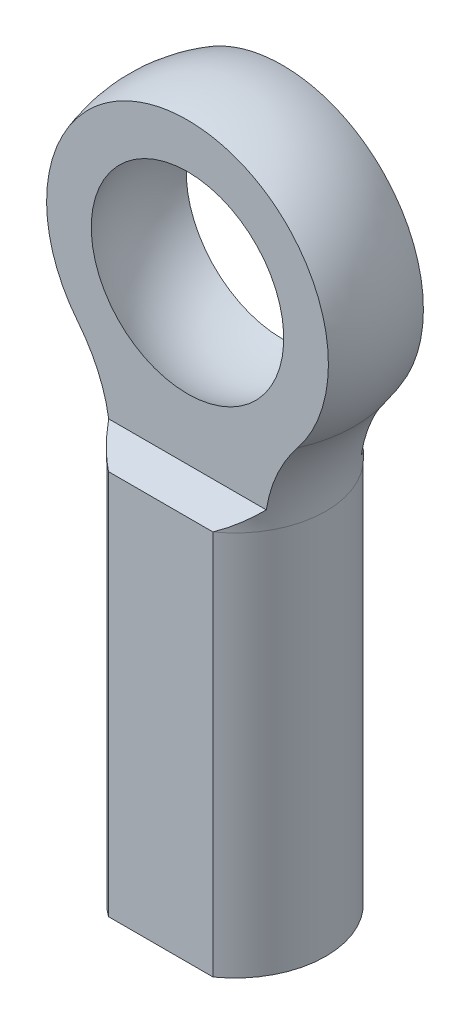
SolidWorks part; units mm, degrees
ref_plane "Front" through (0, 0, 0) normal (0, 0, 1) x (1, 0, 0)
ref_plane "Top" through (0, 0, 0) normal (0, 1, 0) x (1, 0, 0)
ref_plane "Right" through (0, 0, 0) normal (1, 0, 0) x (0, 0, -1)
sketch "Sketch1" plane through (0, 0, 0) normal (0, 0, 1) x (1, 0, 0)
  line L0 (0, 0) -> (0, -26.9875) construction
  line L1 (0, -26.9875) -> (4.7625, -26.9875) construction
  line L2 (4.7625, -26.9875) -> (4.7625, 0) construction
  line L3 (4.7625, 0) -> (0, 0) construction
  line L5 (0, 41.275) -> (0, 0) construction
  line L6 (0, 41.275) -> (14.2875, 41.275) construction
  line L7 (14.2875, 41.275) -> (14.2875, 26.9875) construction
  line L8 (-4.7625, -26.9875) -> (-4.7625, 0) construction
  line L9 (-8.7249, -26.9875) -> (8.7249, -26.9875) construction
  line L10 (8.7249, -26.9875) -> (8.7249, 10.0476) construction
  line L11 (-8.7249, -26.9875) -> (-8.7249, 10.0476) construction
  line L16 (4.8771, -27.4505) -> (4.7625, -27.4505) construction
  line L18 (4.7625, -27.9135) -> (4.7625, -26.9875) construction
  arc A0 (11.5062, 18.5176) -> (0, 41.275) centre (0, 26.9875) ccw construction
  circle A1 centre (0, 26.9875) radius 4.7625 construction
  circle A2 centre (0, 26.9875) radius 10.3124 construction
  circle A3 centre (0, 26.9875) radius 10.828 construction
  arc A4 (8.7249, 10.0476) -> (11.5062, 18.5176) centre (23.0124, 10.0476) cw construction
  point P16 (-4.7625, -16.0514)
  point P30 (4.0751, -27.4505)
  point P31 (-4.7625, -26.9875)
  point P33 (4.7625, -27.4505)
  point P36 (4.8198, -27.4505)
  point P37 (4.7625, -26.9875)
  dimension "Ball Dia" = 20.6248
  dimension "D1" = 21.656
  dimension "ID" = 9.525
  dimension "D2" = 10.9361
  dimension "body width" = 17.4498
  dimension "D4" = 26.9875
  dimension "Thread Dia" = 9.525
  dimension "Overall Width" = 28.575
  dimension "Shank Thread Length" = 26.9875
  dimension "Shank Center Length" = 53.975
sketch "Sketch15" plane through (0, 0, 0) normal (0, 0, 1) x (1, 0, 0)
  line L0 (8.7249, -26.9875) -> (8.7249, 10.0476) construction
  line L1 (4.7625, -26.9875) -> (8.7249, -26.9875)
  line L2 (0, 0) -> (0, 10.0476)
  line L3 (0, 10.0476) -> (8.7249, 10.0476)
  line L4 (8.7249, -26.9875) -> (8.7249, 10.0476)
  line L5 (0, 0) -> (4.7625, 0)
  line L6 (4.7625, 0) -> (4.7625, -26.9875)
revolve "Revolve4" add sketch "Sketch15" angle 360 about L5
sketch "Sketch4" plane through (0, 0, 0) normal (0, 0, 1) x (1, 0, 0)
  line L1 (0, 16.6751) -> (0, 10.0476)
  line L2 (0, 41.275) -> (0, 0) construction
  line L4 (8.7249, 10.0476) -> (-8.7249, 10.0476) construction
  line L5 (0, 41.275) -> (0, 37.2999)
  line L6 (0, 41.275) -> (0, 43.815) construction
  line L7 (8.7249, 10.0476) -> (0, 10.0476)
  arc A0 (11.5062, 18.5176) -> (0, 41.275) centre (0, 26.9875) ccw construction
  arc A1 (11.5062, 18.5176) -> (0, 41.275) centre (0, 26.9875) ccw
  arc A2 (11.5062, 18.5176) -> (8.7249, 10.0476) centre (23.0124, 10.0476) ccw construction
  arc A3 (11.5062, 18.5176) -> (8.7249, 10.0476) centre (23.0124, 10.0476) ccw
  circle A4 centre (0, 26.9875) radius 10.3124 construction
  arc A5 (0, 16.6751) -> (0, 37.2999) centre (0, 26.9875) ccw
  dimension "D1" = 2.54
revolve "Revolve2" add sketch "Sketch4" angle 360 about L6
sketch "Sketch17" plane through (0, 0, 0) normal (1, 0, 0) x (0, 0, -1)
  line L0 (-7.1374, -26.9875) -> (7.1374, -26.9875) construction
  line L1 (-14.2875, 41.275) -> (-7.1374, 41.275)
  line L2 (-14.2875, 41.275) -> (-14.2875, -26.9875)
  line L3 (-14.2875, -26.9875) -> (-7.1374, -26.9875)
  line L4 (-7.1374, 41.275) -> (-7.1374, -26.9875)
  line L5 (7.1374, 41.275) -> (14.2875, 41.275)
  line L6 (7.1374, 41.275) -> (7.1374, -26.9875)
  line L7 (7.1374, -26.9875) -> (14.2875, -26.9875)
  line L8 (14.2875, 41.275) -> (14.2875, -26.9875)
  line L10 (0, 0) -> (0, -26.9875) construction
  line L11 (-8.7249, -26.9875) -> (8.7249, -26.9875) construction
  arc A0 (11.5062, 18.5176) -> (-11.5062, 18.5176) centre (0, 26.9875) ccw construction
  dimension "body flats" = 14.2748
extrude "Extrude3" cut sketch "Sketch17" against normal mid plane 127
sketch "Sketch5" plane through (0, 0, 0) normal (1, 0, 0) x (0, 0, -1)
  line L0 (4.5641, 41.275) -> (12.2174, 41.275)
  line L1 (-4.5641, 41.275) -> (4.5641, 41.275) construction
  line L2 (-4.5641, 41.275) -> (-4.5641, 11.8732)
  line L3 (-7.1374, 10.0476) -> (7.1374, 10.0476) construction
  line L4 (4.5641, 41.275) -> (4.5641, 11.8732)
  line L5 (12.2174, 41.275) -> (12.2174, 10.0476)
  line L6 (12.2174, 10.0476) -> (7.1374, 10.0476)
  line L7 (-7.1374, 10.0476) -> (-12.2174, 10.0476)
  line L8 (-12.2174, 10.0476) -> (-12.2174, 41.275)
  line L9 (-12.2174, 41.275) -> (-4.5641, 41.275)
  line L10 (7.1374, 10.0476) -> (4.5641, 11.8732)
  line L11 (-7.1374, 10.0476) -> (-4.5641, 11.8732)
  line L12 (-4.5641, 11.8732) -> (4.5641, 11.8732) construction
  line L13 (0, -1.1024) -> (0, 11.8732) construction
  line L14 (0, -26.9875) -> (0, 10.0476) construction
  line L15 (-7.1374, 39.3645) -> (-7.1374, 18.5176) construction
  dimension "F" = 9.1281
  dimension "D2" = 1.8256
  dimension "D1" = 5.08
extrude "Cut-Extrude1" cut sketch "Sketch5" against normal through all and the other way through all
ref_point "Point1"
sketch "Sketch18" plane through (0, 0, 0) normal (0, 0, 1) x (1, 0, 0)
  point P0 (0, 26.9875)
equation "\"D1@Sketch1\"=\"Ball Dia@Sketch1\"*1.05"
equation "\"D2@Sketch5\"=\"F@Sketch5\"/5"
